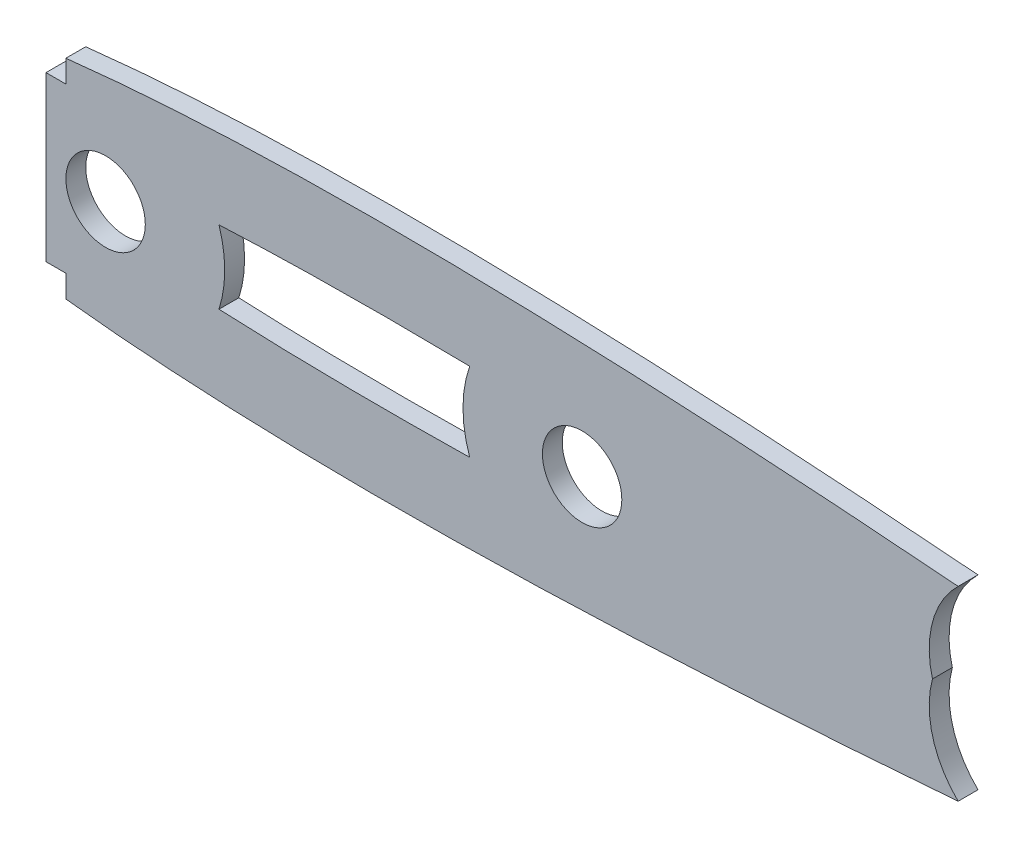
SolidWorks part; units mm, degrees
material "Balsa"
ref_plane "Front Plane" through (0, 0, 0) normal (0, 0, 1) x (1, 0, 0)
ref_plane "Top Plane" through (0, 0, 0) normal (0, 1, 0) x (1, 0, 0)
ref_plane "Right Plane" through (0, 0, 0) normal (1, 0, 0) x (0, 0, -1)
curve "Curve1"
  spline degree 3 poles (318.9616, -0.5388, 0) (318.9616, 0.5388, 0) (317.8871, 0.4072, 0) (316.5257, 0.7904, 0) (314.029, 1.0273, 0) (310.6656, 1.5357, 0) (306.333, 2.103, 0) (301.1081, 2.8022, 0) (295.0047, 3.5926, 0) (288.0667, 4.4725, 0) (280.3349, 5.4267, 0) (271.8575, 6.4421, 0) (262.6867, 7.5062, 0) (252.8789, 8.6045, 0) (242.4947, 9.7236, 0) (231.5982, 10.8496, 0) (220.2564, 11.9679, 0) (208.5394, 13.0629, 0) (196.5193, 14.1202, 0) (184.2704, 15.122, 0) (171.8679, 16.0521, 0) (159.3884, 16.8933, 0) (146.9087, 17.6278, 0) (134.5058, 18.2372, 0) (122.2562, 18.7052, 0) (110.2351, 19.0165, 0) (98.5168, 19.156, 0) (87.1732, 19.1125, 0) (76.2743, 18.8777, 0) (65.8873, 18.4456, 0) (56.076, 17.8151, 0) (46.9007, 16.9881, 0) (38.4176, 15.971, 0) (30.6784, 14.7725, 0) (23.73, 13.4051, 0) (17.6131, 11.8842, 0) (12.3624, 10.2248, 0) (8.0047, 8.4423, 0) (4.5539, 6.5486, 0) (2.0152, 4.5401, 0) (0.3892, 2.3682, 0) (-0.1814, 0, 0) (0.3892, -2.3682, 0) (2.0152, -4.5401, 0) (4.5539, -6.5486, 0) (8.0047, -8.4423, 0) (12.3624, -10.2248, 0) (17.6131, -11.8842, 0) (23.73, -13.4051, 0) (30.6784, -14.7725, 0) (38.4176, -15.971, 0) (46.9007, -16.9881, 0) (56.076, -17.8151, 0) (65.8873, -18.4456, 0) (76.2743, -18.8777, 0) (87.1732, -19.1125, 0) (98.5168, -19.156, 0) (110.2351, -19.0165, 0) (122.2562, -18.7052, 0) (134.5058, -18.2372, 0) (146.9087, -17.6278, 0) (159.3884, -16.8933, 0) (171.8679, -16.0521, 0) (184.2704, -15.122, 0) (196.5193, -14.1202, 0) (208.5394, -13.0629, 0) (220.2564, -11.9679, 0) (231.5982, -10.8496, 0) (242.4947, -9.7236, 0) (252.8789, -8.6045, 0) (262.6867, -7.5062, 0) (271.8575, -6.4421, 0) (280.3349, -5.4267, 0) (288.0667, -4.4725, 0) (295.0047, -3.5926, 0) (301.1081, -2.8022, 0) (306.333, -2.103, 0) (310.6656, -1.5357, 0) (314.029, -1.0273, 0) (316.5257, -0.7904, 0) (317.8871, -0.4072, 0) (318.9616, -0.5388, 0) (318.9616, 0.5388, 0) (317.8871, 0.4072, 0) knots -0.004279 -0.001997 -0.001234 0 0.000762 0.003045 0.006832 0.012101 0.018818 0.026939 0.036415 0.047185 0.05918 0.072328 0.086544 0.101741 0.117823 0.134691 0.15224 0.170361 0.188941 0.207865 0.227016 0.246276 0.265525 0.284645 0.30352 0.322035 0.340078 0.357543 0.374325 0.39033 0.405464 0.419644 0.432793 0.444844 0.455738 0.465429 0.473886 0.481102 0.487102 0.491975 0.495931 0.499383 0.502835 0.50679 0.511664 0.517664 0.524879 0.533337 0.543028 0.553922 0.565972 0.579122 0.593302 0.608436 0.62444 0.641223 0.658687 0.676731 0.695245 0.714121 0.733241 0.75249 0.77175 0.7909 0.809825 0.828404 0.846525 0.864074 0.880942 0.897025 0.912222 0.926438 0.939585 0.951581 0.962351 0.971826 0.979948 0.986664 0.991933 0.995721 0.998003 0.998766 1 1.000762 1.003045 1.006832 periodic
sketch "Sketch2" plane through (0, 0, 0) normal (0, 0, 1) x (1, 0, 0)
  spline S0 degree 3 poles (318.9616, -0.5388) (318.9616, 0.5388) (317.8871, 0.4072) (316.5257, 0.7904) (314.029, 1.0273) (310.6656, 1.5357) (306.333, 2.103) (301.1081, 2.8022) (295.0047, 3.5926) (288.0667, 4.4725) (280.3349, 5.4267) (271.8575, 6.4421) (262.6867, 7.5062) (252.8789, 8.6045) (242.4947, 9.7236) (231.5982, 10.8496) (220.2564, 11.9679) (208.5394, 13.0629) (196.5193, 14.1202) (184.2704, 15.122) (171.8679, 16.0521) (159.3884, 16.8933) (146.9087, 17.6278) (134.5058, 18.2372) (122.2562, 18.7052) (110.2351, 19.0165) (98.5168, 19.156) (87.1732, 19.1125) (76.2743, 18.8777) (65.8873, 18.4456) (56.076, 17.8151) (46.9007, 16.9881) (38.4176, 15.971) (30.6784, 14.7725) (23.73, 13.4051) (17.6131, 11.8842) (12.3624, 10.2248) (8.0047, 8.4423) (4.5539, 6.5486) (2.0152, 4.5401) (0.3892, 2.3682) (-0.1814, 0) (0.3892, -2.3682) (2.0152, -4.5401) (4.5539, -6.5486) (8.0047, -8.4423) (12.3624, -10.2248) (17.6131, -11.8842) (23.73, -13.4051) (30.6784, -14.7725) (38.4176, -15.971) (46.9007, -16.9881) (56.076, -17.8151) (65.8873, -18.4456) (76.2743, -18.8777) (87.1732, -19.1125) (98.5168, -19.156) (110.2351, -19.0165) (122.2562, -18.7052) (134.5058, -18.2372) (146.9087, -17.6278) (159.3884, -16.8933) (171.8679, -16.0521) (184.2704, -15.122) (196.5193, -14.1202) (208.5394, -13.0629) (220.2564, -11.9679) (231.5982, -10.8496) (242.4947, -9.7236) (252.8789, -8.6045) (262.6867, -7.5062) (271.8575, -6.4421) (280.3349, -5.4267) (288.0667, -4.4725) (295.0047, -3.5926) (301.1081, -2.8022) (306.333, -2.103) (310.6656, -1.5357) (314.029, -1.0273) (316.5257, -0.7904) (317.8871, -0.4072) (318.9616, -0.5388) (318.9616, 0.5388) (317.8871, 0.4072) knots -0.004279 -0.001997 -0.001234 0 0.000762 0.003045 0.006832 0.012101 0.018818 0.026939 0.036415 0.047185 0.05918 0.072328 0.086544 0.101741 0.117823 0.134691 0.15224 0.170361 0.188941 0.207865 0.227016 0.246276 0.265525 0.284645 0.30352 0.322035 0.340078 0.357543 0.374325 0.39033 0.405464 0.419644 0.432793 0.444844 0.455738 0.465429 0.473886 0.481102 0.487102 0.491975 0.495931 0.499383 0.502835 0.50679 0.511664 0.517664 0.524879 0.533337 0.543028 0.553922 0.565972 0.579122 0.593302 0.608436 0.62444 0.641223 0.658687 0.676731 0.695245 0.714121 0.733241 0.75249 0.77175 0.7909 0.809825 0.828404 0.846525 0.864074 0.880942 0.897025 0.912222 0.926438 0.939585 0.951581 0.962351 0.971826 0.979948 0.986664 0.991933 0.995721 0.998003 0.998766 1 1.000762 1.003045 1.006832 only from (318.77, 0.4017) to (318.77, 0.4017) construction
  spline S1 degree 3 poles (318.9616, -0.5388) (318.9616, 0.5388) (317.8871, 0.4072) (316.5257, 0.7904) (314.029, 1.0273) (310.6656, 1.5357) (306.333, 2.103) (301.1081, 2.8022) (295.0047, 3.5926) (288.0667, 4.4725) (280.3349, 5.4267) (271.8575, 6.4421) (262.6867, 7.5062) (252.8789, 8.6045) (242.4947, 9.7236) (231.5982, 10.8496) (220.2564, 11.9679) (208.5394, 13.0629) (196.5193, 14.1202) (184.2704, 15.122) (171.8679, 16.0521) (159.3884, 16.8933) (146.9087, 17.6278) (134.5058, 18.2372) (122.2562, 18.7052) (110.2351, 19.0165) (98.5168, 19.156) (87.1732, 19.1125) (76.2743, 18.8777) (65.8873, 18.4456) (56.076, 17.8151) (46.9007, 16.9881) (38.4176, 15.971) (30.6784, 14.7725) (23.73, 13.4051) (17.6131, 11.8842) (12.3624, 10.2248) (8.0047, 8.4423) (4.5539, 6.5486) (2.0152, 4.5401) (0.3892, 2.3682) (-0.1814, 0) (0.3892, -2.3682) (2.0152, -4.5401) (4.5539, -6.5486) (8.0047, -8.4423) (12.3624, -10.2248) (17.6131, -11.8842) (23.73, -13.4051) (30.6784, -14.7725) (38.4176, -15.971) (46.9007, -16.9881) (56.076, -17.8151) (65.8873, -18.4456) (76.2743, -18.8777) (87.1732, -19.1125) (98.5168, -19.156) (110.2351, -19.0165) (122.2562, -18.7052) (134.5058, -18.2372) (146.9087, -17.6278) (159.3884, -16.8933) (171.8679, -16.0521) (184.2704, -15.122) (196.5193, -14.1202) (208.5394, -13.0629) (220.2564, -11.9679) (231.5982, -10.8496) (242.4947, -9.7236) (252.8789, -8.6045) (262.6867, -7.5062) (271.8575, -6.4421) (280.3349, -5.4267) (288.0667, -4.4725) (295.0047, -3.5926) (301.1081, -2.8022) (306.333, -2.103) (310.6656, -1.5357) (314.029, -1.0273) (316.5257, -0.7904) (317.8871, -0.4072) (318.9616, -0.5388) (318.9616, 0.5388) (317.8871, 0.4072) knots -0.004279 -0.001997 -0.001234 0 0.000762 0.003045 0.006832 0.012101 0.018818 0.026939 0.036415 0.047185 0.05918 0.072328 0.086544 0.101741 0.117823 0.134691 0.15224 0.170361 0.188941 0.207865 0.227016 0.246276 0.265525 0.284645 0.30352 0.322035 0.340078 0.357543 0.374325 0.39033 0.405464 0.419644 0.432793 0.444844 0.455738 0.465429 0.473886 0.481102 0.487102 0.491975 0.495931 0.499383 0.502835 0.50679 0.511664 0.517664 0.524879 0.533337 0.543028 0.553922 0.565972 0.579122 0.593302 0.608436 0.62444 0.641223 0.658687 0.676731 0.695245 0.714121 0.733241 0.75249 0.77175 0.7909 0.809825 0.828404 0.846525 0.864074 0.880942 0.897025 0.912222 0.926438 0.939585 0.951581 0.962351 0.971826 0.979948 0.986664 0.991933 0.995721 0.998003 0.998766 1 1.000762 1.003045 1.006832 only from (318.77, 0.4017) to (318.77, 0.4017)
extrude "Boss-Extrude1" add sketch "Sketch2" along normal blind 3.175
sketch "Sketch3" plane through (0, 0, 3.175) normal (0, 0, 1) x (1, 0, 0)
  circle A0 centre (50.8, 0) radius 6.35
  circle A1 centre (127, 0) radius 6.35
  dimension "D1" = 12.7
  dimension "D2" = 12.7
  dimension "D3" = 50.8
  dimension "D4" = 127
  dimension "D5" = 0
  dimension "D6" = 0
extrude "Cut-Extrude1" cut sketch "Sketch3" against normal through all
sketch "Sketch4" plane through (0, 0, 3.175) normal (0, 0, 1) x (1, 0, 0)
  line L0 (44.4469, 16.6766) -> (44.4469, 13.0978)
  line L1 (41.2719, 13.0978) -> (41.2719, -13.0978)
  line L2 (41.2719, -13.0978) -> (44.4469, -13.0978)
  line L3 (41.2719, 13.0978) -> (44.4469, 13.0978)
  line L4 (44.4469, -13.0978) -> (44.4469, -16.6766)
  spline S0 degree 3 poles (318.9616, -0.5388) (318.9616, 0.5388) (317.8871, 0.4072) (316.5257, 0.7904) (314.029, 1.0273) (310.6656, 1.5357) (306.333, 2.103) (301.1081, 2.8022) (295.0047, 3.5926) (288.0667, 4.4725) (280.3349, 5.4267) (271.8575, 6.4421) (262.6867, 7.5062) (252.8789, 8.6045) (242.4947, 9.7236) (231.5982, 10.8496) (220.2564, 11.9679) (208.5394, 13.0629) (196.5193, 14.1202) (184.2704, 15.122) (171.8679, 16.0521) (159.3884, 16.8933) (146.9087, 17.6278) (134.5058, 18.2372) (122.2562, 18.7052) (110.2351, 19.0165) (98.5168, 19.156) (87.1732, 19.1125) (76.2743, 18.8777) (65.8873, 18.4456) (56.076, 17.8151) (46.9007, 16.9881) (38.4176, 15.971) (30.6784, 14.7725) (23.73, 13.4051) (17.6131, 11.8842) (12.3624, 10.2248) (8.0047, 8.4423) (4.5539, 6.5486) (2.0152, 4.5401) (0.3892, 2.3682) (-0.1814, 0) (0.3892, -2.3682) (2.0152, -4.5401) (4.5539, -6.5486) (8.0047, -8.4423) (12.3624, -10.2248) (17.6131, -11.8842) (23.73, -13.4051) (30.6784, -14.7725) (38.4176, -15.971) (46.9007, -16.9881) (56.076, -17.8151) (65.8873, -18.4456) (76.2743, -18.8777) (87.1732, -19.1125) (98.5168, -19.156) (110.2351, -19.0165) (122.2562, -18.7052) (134.5058, -18.2372) (146.9087, -17.6278) (159.3884, -16.8933) (171.8679, -16.0521) (184.2704, -15.122) (196.5193, -14.1202) (208.5394, -13.0629) (220.2564, -11.9679) (231.5982, -10.8496) (242.4947, -9.7236) (252.8789, -8.6045) (262.6867, -7.5062) (271.8575, -6.4421) (280.3349, -5.4267) (288.0667, -4.4725) (295.0047, -3.5926) (301.1081, -2.8022) (306.333, -2.103) (310.6656, -1.5357) (314.029, -1.0273) (316.5257, -0.7904) (317.8871, -0.4072) (318.9616, -0.5388) (318.9616, 0.5388) (317.8871, 0.4072) knots -0.004279 -0.001997 -0.001234 0 0.000762 0.003045 0.006832 0.012101 0.018818 0.026939 0.036415 0.047185 0.05918 0.072328 0.086544 0.101741 0.117823 0.134691 0.15224 0.170361 0.188941 0.207865 0.227016 0.246276 0.265525 0.284645 0.30352 0.322035 0.340078 0.357543 0.374325 0.39033 0.405464 0.419644 0.432793 0.444844 0.455738 0.465429 0.473886 0.481102 0.487102 0.491975 0.495931 0.499383 0.502835 0.50679 0.511664 0.517664 0.524879 0.533337 0.543028 0.553922 0.565972 0.579122 0.593302 0.608436 0.62444 0.641223 0.658687 0.676731 0.695245 0.714121 0.733241 0.75249 0.77175 0.7909 0.809825 0.828404 0.846525 0.864074 0.880942 0.897025 0.912222 0.926438 0.939585 0.951581 0.962351 0.971826 0.979948 0.986664 0.991933 0.995721 0.998003 0.998766 1 1.000762 1.003045 1.006832 only from (318.77, 0.4017) to (318.77, 0.4017) construction
  spline S1 degree 3 poles (44.4469, 16.6766) (42.3575, 16.4398) (37.6765, 15.8562) (30.6784, 14.7725) (23.73, 13.4051) (17.6131, 11.8842) (12.3624, 10.2248) (8.0047, 8.4423) (4.5539, 6.5486) (2.0152, 4.5401) (0.3892, 2.3682) (-0.1814, 0) (0.3892, -2.3682) (2.0152, -4.5401) (4.5539, -6.5486) (8.0047, -8.4423) (12.3624, -10.2248) (17.6131, -11.8842) (23.73, -13.4051) (30.6784, -14.7725) (37.6765, -15.8562) (42.3575, -16.4398) (44.4469, -16.6766) knots 0.4231 0.4231 0.4231 0.4231 0.432793 0.444844 0.455738 0.465429 0.473886 0.481102 0.487102 0.491975 0.495931 0.499383 0.502835 0.50679 0.511664 0.517664 0.524879 0.533337 0.543028 0.553922 0.565972 0.575665 0.575665 0.575665 0.575665
  dimension "D2" = 3.175
  dimension "D1" = 3.5788
  dimension "D3" = 41.2719
  dimension "D4" = 3.175
  dimension "D5" = 3.5788
extrude "Cut-Extrude2" cut sketch "Sketch4" against normal through all
sketch "Sketch5" plane through (0, 0, 3.175) normal (0, 0, 1) x (1, 0, 0)
  line L0 (1.7463, 0) -> (-1.7463, 0) construction
  line L1 (183.0237, 0) -> (228.7437, 0) construction
  line L4 (183.0237, 0) -> (202.931, 5.3341) construction
  line L5 (183.0237, 0) -> (200.3978, -4.6554) construction
  line L6 (188.4413, 14.7763) -> (187.3498, 15.0894)
  line L7 (188.4413, -14.7763) -> (187.2309, -14.9772)
  arc A1 (187.3498, 15.0894) -> (183.0237, 0) centre (197.7444, 3.9444) ccw
  arc A2 (183.0237, 0) -> (187.2309, -14.9772) centre (197.7444, -3.9444) ccw
  spline S0 degree 3 poles (318.9616, -0.5388) (318.9616, 0.5388) (317.8871, 0.4072) (316.5257, 0.7904) (314.029, 1.0273) (310.6656, 1.5357) (306.333, 2.103) (301.1081, 2.8022) (295.0047, 3.5926) (288.0667, 4.4725) (280.3349, 5.4267) (271.8575, 6.4421) (262.6867, 7.5062) (252.8789, 8.6045) (242.4947, 9.7236) (231.5982, 10.8496) (220.2564, 11.9679) (208.5394, 13.0629) (196.5193, 14.1202) (184.2704, 15.122) (171.8679, 16.0521) (159.3884, 16.8933) (146.9087, 17.6278) (134.5058, 18.2372) (122.2562, 18.7052) (110.2351, 19.0165) (98.5168, 19.156) (87.1732, 19.1125) (76.2743, 18.8777) (65.8873, 18.4456) (56.076, 17.8151) (46.9007, 16.9881) (38.4176, 15.971) (30.6784, 14.7725) (23.73, 13.4051) (17.6131, 11.8842) (12.3624, 10.2248) (8.0047, 8.4423) (4.5539, 6.5486) (2.0152, 4.5401) (0.3892, 2.3682) (-0.1814, 0) (0.3892, -2.3682) (2.0152, -4.5401) (4.5539, -6.5486) (8.0047, -8.4423) (12.3624, -10.2248) (17.6131, -11.8842) (23.73, -13.4051) (30.6784, -14.7725) (38.4176, -15.971) (46.9007, -16.9881) (56.076, -17.8151) (65.8873, -18.4456) (76.2743, -18.8777) (87.1732, -19.1125) (98.5168, -19.156) (110.2351, -19.0165) (122.2562, -18.7052) (134.5058, -18.2372) (146.9087, -17.6278) (159.3884, -16.8933) (171.8679, -16.0521) (184.2704, -15.122) (196.5193, -14.1202) (208.5394, -13.0629) (220.2564, -11.9679) (231.5982, -10.8496) (242.4947, -9.7236) (252.8789, -8.6045) (262.6867, -7.5062) (271.8575, -6.4421) (280.3349, -5.4267) (288.0667, -4.4725) (295.0047, -3.5926) (301.1081, -2.8022) (306.333, -2.103) (310.6656, -1.5357) (314.029, -1.0273) (316.5257, -0.7904) (317.8871, -0.4072) (318.9616, -0.5388) (318.9616, 0.5388) (317.8871, 0.4072) knots -0.004279 -0.001997 -0.001234 0 0.000762 0.003045 0.006832 0.012101 0.018818 0.026939 0.036415 0.047185 0.05918 0.072328 0.086544 0.101741 0.117823 0.134691 0.15224 0.170361 0.188941 0.207865 0.227016 0.246276 0.265525 0.284645 0.30352 0.322035 0.340078 0.357543 0.374325 0.39033 0.405464 0.419644 0.432793 0.444844 0.455738 0.465429 0.473886 0.481102 0.487102 0.491975 0.495931 0.499383 0.502835 0.50679 0.511664 0.517664 0.524879 0.533337 0.543028 0.553922 0.565972 0.579122 0.593302 0.608436 0.62444 0.641223 0.658687 0.676731 0.695245 0.714121 0.733241 0.75249 0.77175 0.7909 0.809825 0.828404 0.846525 0.864074 0.880942 0.897025 0.912222 0.926438 0.939585 0.951581 0.962351 0.971826 0.979948 0.986664 0.991933 0.995721 0.998003 0.998766 1 1.000762 1.003045 1.006832 only from (44.4469, -16.6766) to (44.4469, 16.6766) construction
  spline S1 degree 3 poles (188.4413, -14.7763) (191.1589, -14.5572) (197.8927, -13.9994) (208.5394, -13.0629) (220.2564, -11.9679) (231.5982, -10.8496) (242.4947, -9.7236) (252.8789, -8.6045) (262.6867, -7.5062) (271.8575, -6.4421) (280.3349, -5.4267) (288.0667, -4.4725) (295.0047, -3.5926) (301.1081, -2.8022) (306.333, -2.103) (310.6656, -1.5357) (314.029, -1.0273) (316.5257, -0.7904) (317.8871, -0.4072) (318.9616, -0.5388) (318.9616, 0.5388) (317.8871, 0.4072) (316.5257, 0.7904) (314.029, 1.0273) (310.6656, 1.5357) (306.333, 2.103) (301.1081, 2.8022) (295.0047, 3.5926) (288.0667, 4.4725) (280.3349, 5.4267) (271.8575, 6.4421) (262.6867, 7.5062) (252.8789, 8.6045) (242.4947, 9.7236) (231.5982, 10.8496) (220.2564, 11.9679) (208.5394, 13.0629) (197.8927, 13.9994) (191.1589, 14.5572) (188.4413, 14.7763) knots 0.797256 0.797256 0.797256 0.797256 0.809825 0.828404 0.846525 0.864074 0.880942 0.897025 0.912222 0.926438 0.939585 0.951581 0.962351 0.971826 0.979948 0.986664 0.991933 0.995721 0.998003 0.998766 1 1.000762 1.003045 1.006832 1.012101 1.018818 1.026939 1.036415 1.047185 1.05918 1.072328 1.086544 1.101741 1.117823 1.134691 1.15224 1.170361 1.188941 1.20151 1.20151 1.20151 1.20151
  point P0 (318.9137, 0)
  point P1 (187.2309, -14.9772)
  point P16 (187.1314, 14.8815)
  point P17 (187.1314, 14.8815)
  point P19 (187.3498, 15.0894)
  dimension "D5" = 30.48
  dimension "D6" = 30.48
  dimension "D1" = 135.89
  dimension "D3" = 15
  dimension "D4" = 15
extrude "Cut-Extrude3" cut sketch "Sketch5" against normal through all
sketch "Sketch7" plane through (0, 0, 3.175) normal (0, 0, 1) x (1, 0, 0)
  arc A6 (68.9314, -5.8443) -> (68.9314, 5.8443) centre (50.8, 0) ccw
  arc A7 (109.025, 6.3089) -> (109.025, -6.3089) centre (127, 0) ccw
  spline S31 degree 3 poles (68.9314, -5.8443) (71.4499, -5.9638) (73.9743, -6.0625) (81.6633, -6.3071) (86.8411, -6.3952) (97.2187, -6.4498) (102.4187, -6.4161) (108.092, -6.325) (108.5585, -6.3171) (109.025, -6.3089) knots 0.188745 0.188745 0.188745 0.188745 0.25 0.25 0.375 0.375 0.5 0.5 0.511197 0.511197 0.511197 0.511197
  spline S32 degree 3 poles (109.025, 6.3089) (108.5585, 6.3171) (108.092, 6.325) (102.4187, 6.4161) (97.2187, 6.4498) (86.8411, 6.3952) (81.6633, 6.3071) (73.9743, 6.0625) (71.4499, 5.9638) (68.9314, 5.8443) knots 0.488803 0.488803 0.488803 0.488803 0.5 0.5 0.625 0.625 0.75 0.75 0.811255 0.811255 0.811255 0.811255
extrude "Cut-Extrude4" cut sketch "Sketch7" against normal through all
